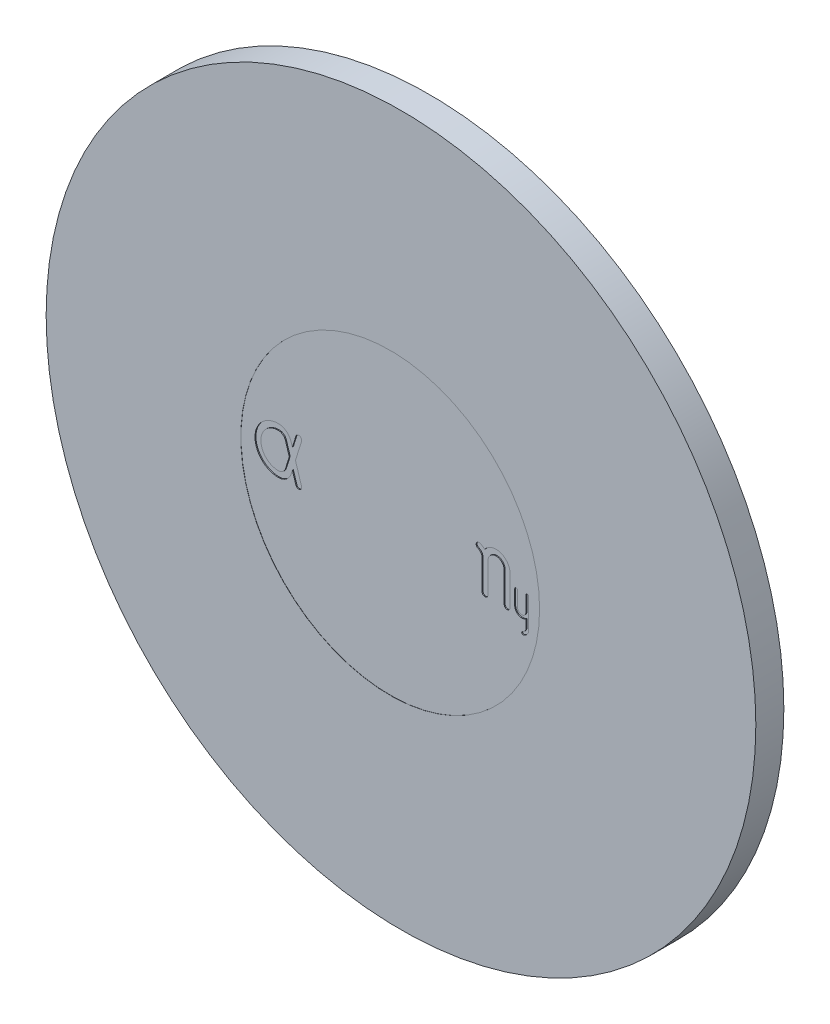
SolidWorks part; units mm, degrees
ref_plane "Спереди" through (0, 0, 0) normal (0, 0, 1) x (1, 0, 0)
ref_plane "Сверху" through (0, 0, 0) normal (0, 1, 0) x (1, 0, 0)
ref_plane "Справа" through (0, 0, 0) normal (1, 0, 0) x (0, 0, -1)
sketch "Эскиз1" plane through (0, 0, 0) normal (0, 0, 1) x (1, 0, 0)
  circle A0 centre (1.1554, 0.8345) radius 38
  dimension "D1" = 76
extrude "Вытянуть1" add sketch "Эскиз1" along normal blind 3
sketch "Эскиз2" plane through (0, 0, 3) normal (0, 0, 1) x (1, 0, 0)
  circle A0 centre (0, 0) radius 16
  dimension "D1" = 32
extrude "Вытянуть2" cut sketch "Эскиз2" against normal blind 0.02
sketch "Эскиз3" plane through (0, 0, 2.98) normal (0, 0, 1) x (1, 0, 0)
  line L0 (0, 0) -> (54.7035, 0) construction
  line L1 (0, 0) -> (0, 49.437) construction
  line L2 (-10.6351, 2.1964) -> (-10.4976, 1.7564)
  line L3 (-14.5, 3.2) -> (-12, 3.2) construction
  line L4 (-14.5, 3.2) -> (-14.5, 0.7) construction
  line L5 (-12, -1.8) -> (-9.5, -1.8) construction
  line L6 (-9.5, 3.2) -> (-9.5, -1.8) construction
  line L7 (-10.6351, -0.7964) -> (-10.4976, -0.3564)
  line L8 (-30.8737, 0.7) -> (-25.4406, 0.7) construction
  line L9 (-11.2371, -0.611) -> (-10.8276, 0.7)
  line L10 (-11.2371, 2.011) -> (-10.8276, 0.7)
  line L11 (-10.1676, 0.7) -> (-9.5143, 2.7911)
  line L12 (9.815, 1.705) -> (9.815, 1.7)
  line L13 (12.185, 1.7) -> (12.185, -1.485)
  line L14 (-10.4976, -0.3564) -> (-10.1157, -1.5789)
  line L15 (-10.4976, 1.7564) -> (-10.1157, 2.9789)
  line L16 (-10.1676, 0.7) -> (-9.5143, -1.3911)
  line L17 (9.815, 1.7) -> (9.815, -1.485)
  line L18 (10.13, -1.485) -> (10.13, 1.705) construction
  line L19 (12.815, 1.7) -> (12.815, -1.485)
  line L20 (10.445, 1.7) -> (10.445, -1.485)
  line L21 (9.815, 1.7) -> (9.815, -1.8) construction
  line L22 (10.445, 1.7) -> (10.445, -1.8) construction
  line L23 (12.815, 1.7) -> (12.815, -1.8) construction
  line L24 (12.185, 1.7) -> (12.185, -1.8) construction
  line L25 (10.13, -1.8) -> (12.5, -1.8) construction
  line L26 (9.5, 4.6337) -> (9.5, -4.3602) construction
  line L27 (-12, 1.77) -> (-12, -3.0023) construction
  line L28 (14.815, 0.55) -> (14.815, -2.55)
  line L29 (13.615, 0.55) -> (13.615, -1.05)
  line L30 (13.315, 0.55) -> (13.315, -1.05)
  line L31 (14.515, 0.55) -> (14.515, -1.05)
  line L33 (14.515, -1.65) -> (14.515, -2.55)
  line L34 (14.815, 0.7) -> (14.815, -2.55) construction
  line L35 (14.515, 0.7) -> (14.515, -2.55) construction
  line L36 (13.615, 0.7) -> (13.615, -1.05) construction
  line L37 (13.315, 0.7) -> (13.315, -1.05) construction
  arc A0 (-14.5, 0.7) -> (-12, -1.8) centre (-12, 0.7) ccw
  arc A1 (-12, 3.2) -> (-14.5, 0.7) centre (-12, 0.7) ccw
  arc A2 (-12, 3.2) -> (-10.6351, 2.1964) centre (-12, 1.77) cw
  arc A3 (-12, -1.8) -> (-10.6351, -0.7964) centre (-12, -0.37) ccw
  arc A4 (-12.0014, 2.57) -> (-11.2371, 2.011) centre (-12, 1.77) cw
  arc A5 (-12.0014, 2.57) -> (-13.87, 0.7007) centre (-12, 0.7) ccw
  arc A6 (-13.87, 0.7007) -> (-12.0014, -1.17) centre (-12, 0.7) ccw
  arc A7 (-12.0014, -1.17) -> (-11.2371, -0.611) centre (-12, -0.37) ccw
  arc A8 (-9.5143, 2.7911) -> (-10.1157, 2.9789) centre (-9.815, 2.885) ccw
  arc A9 (-9.5143, -1.3911) -> (-10.1157, -1.5789) centre (-9.815, -1.485) cw
  arc A10 (12.815, 1.7) -> (10.0974, 2.576) centre (11.315, 1.7) ccw
  arc A11 (9.3939, 2.3029) -> (9.815, 1.705) centre (9.18, 1.705) cw
  arc A12 (12.185, 1.7) -> (10.445, 1.7) centre (11.315, 1.7) ccw
  arc A13 (9.815, -1.485) -> (10.445, -1.485) centre (10.13, -1.485) ccw
  arc A14 (12.185, -1.485) -> (12.815, -1.485) centre (12.5, -1.485) ccw
  arc A15 (9.5, 2.5995) -> (10.13, 1.705) centre (9.18, 1.705) cw construction
  arc A16 (9.6061, 2.8961) -> (10.0974, 2.576) centre (9.18, 1.705) cw
  circle A17 centre (1.1554, 0.8345) radius 37.37
  circle A18 centre (1.1554, 0.8345) radius 37.37
  arc A19 (9.3939, 2.3029) -> (9.6061, 2.8961) centre (9.5, 2.5995) cw
  arc A20 (14.815, -2.55) -> (14.2525, -3.2762) centre (14.065, -2.55) cw
  arc A21 (13.315, -1.05) -> (14.515, -1.65) centre (14.065, -1.05) ccw
  arc A22 (13.615, -1.05) -> (14.515, -1.05) centre (14.065, -1.05) ccw
  arc A23 (12.815, 1.7) -> (9.815, 1.7) centre (11.315, 1.7) ccw construction
  arc A24 (9.6061, 2.8961) -> (10.445, 1.705) centre (9.18, 1.705) cw construction
  arc A25 (14.515, -2.55) -> (14.1775, -2.9857) centre (14.065, -2.55) cw
  arc A26 (13.615, 0.55) -> (13.315, 0.55) centre (13.465, 0.55) ccw
  arc A27 (14.815, 0.55) -> (14.515, 0.55) centre (14.665, 0.55) ccw
  arc A28 (14.1775, -2.9857) -> (14.2525, -3.2762) centre (14.215, -3.1309) ccw
  arc A30 (14.815, -2.55) -> (14.065, -3.3) centre (14.065, -2.55) cw construction
  arc A31 (14.515, -2.55) -> (14.065, -3) centre (14.065, -2.55) cw construction
  arc A32 (13.315, -1.05) -> (14.815, -1.05) centre (14.065, -1.05) ccw construction
  point P10 (-14.5, -1.8)
  point P16 (28.8732, 2.57)
  point P32 (-27.8907, -1.9721)
  point P37 (29.4608, 3.4705)
  point P55 (28.7441, 3.1866)
  point P84 (32.6579, -3.3)
  dimension "D4" = 2.5
  dimension "D5" = 2.5
  dimension "D7" = 1.43
  dimension "D18" = 0.63
  dimension "D17" = 3.19
  dimension "D19" = 0.95
  dimension "D25" = 0.87
  dimension "D26" = 0.63
  dimension "D28" = 1.87
  dimension "D29" = 1.87
  dimension "D34" = 0.75
  dimension "D33" = 3.6809
  dimension "D35" = 0.75
  dimension "D1" = 5
  dimension "D2" = 5
  dimension "D3" = 1.8
  dimension "D6" = 2.5
  dimension "D8" = 5
  dimension "D9" = 2.5
  dimension "D10" = 5
  dimension "D11" = 0.63
  dimension "D12" = 0.63
  dimension "D13" = 14.5
  dimension "D14" = 3.185
  dimension "D15" = 1.8
  dimension "D16" = 9.5
  dimension "D24" = 2.37
  dimension "D27" = 0.63
  dimension "D30" = 0.3
  dimension "D31" = 0.3
  dimension "D32" = 1.5
  dimension "D36" = 1.05
  dimension "D37" = 0.5
  dimension "D20" = 0.63
  dimension "D21" = 0.63
  dimension "D22" = 0.315
  dimension "D23" = 0.315
extrude "Вытянуть3" cut sketch "Эскиз3" against normal blind 0.1
